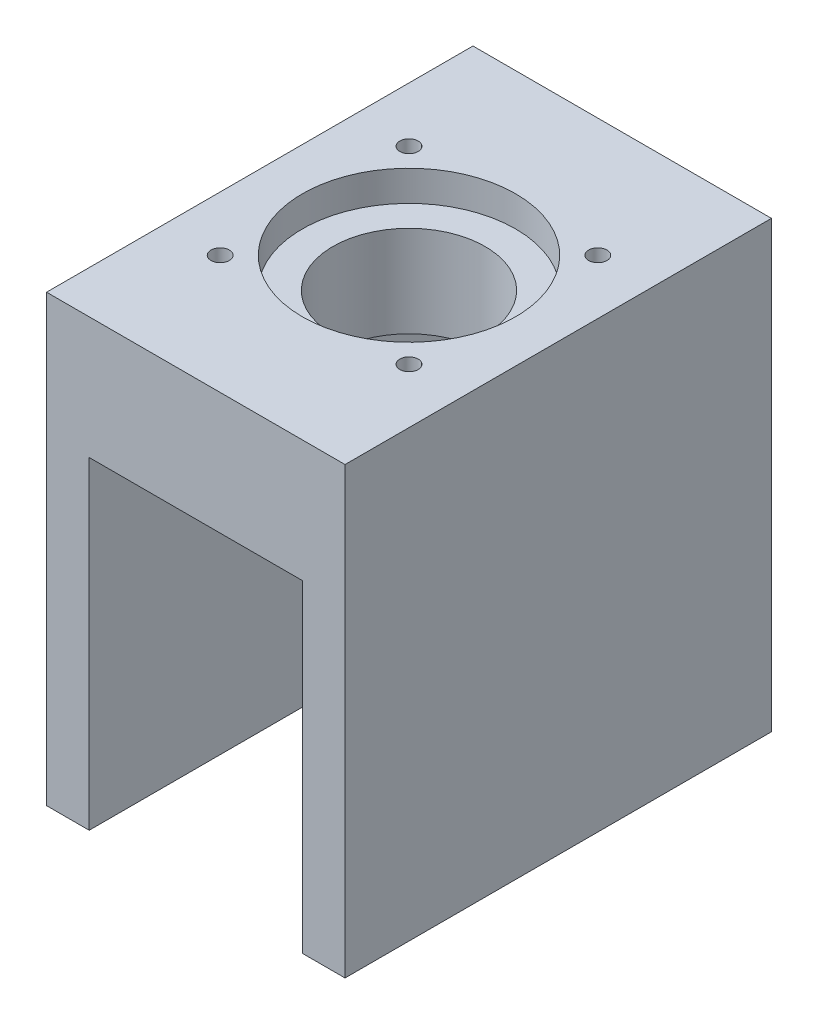
SolidWorks part; units mm, degrees
ref_plane "Front Plane" through (0, 0, 0) normal (0, 0, 1) x (1, 0, 0)
ref_plane "Top Plane" through (0, 0, 0) normal (0, 1, 0) x (1, 0, 0)
ref_plane "Right Plane" through (0, 0, 0) normal (1, 0, 0) x (0, 0, -1)
sketch "Sketch1" plane through (0, 0, 0) normal (0, 1, 0) x (1, 0, 0)
  line L1 (24.5, -35) -> (-24.5, -35)
  line L2 (24.5, -35) -> (24.5, 35)
  line L3 (24.5, 35) -> (-24.5, 35)
  line L4 (-24.5, -35) -> (-24.5, 35)
  line L5 (24.5, -35) -> (-24.5, 35) construction
  line L6 (24.5, 35) -> (-24.5, -35) construction
  point P0 (0, 0)
  dimension "D1" = 49
  dimension "D2" = 70
extrude "Boss-Extrude1" add sketch "Sketch1" along normal blind 20
sketch "Sketch3" plane through (0, 20, 0) normal (0, 1, 0) x (1, 0, 0)
  circle A0 centre (0, 0) radius 12.5
  dimension "D1" = 25
extrude "Cut-Extrude1" cut sketch "Sketch3" against normal blind 70
sketch "Sketch4" plane through (0, 0, 0) normal (0, -1, 0) x (1, 0, 0)
  circle A0 centre (-15.5, 15.5) radius 1.5
  circle A1 centre (15.5, 15.5) radius 1.5
  circle A2 centre (15.5, -15.5) radius 1.5
  circle A3 centre (-15.5, -15.5) radius 1.5
  point P12 (0, 0)
  dimension "D1" = 4
extrude "Cut-Extrude2" cut sketch "Sketch4" against normal through all
sketch "Sketch5" plane through (0, 20, 0) normal (0, 1, 0) x (1, 0, 0)
  circle A0 centre (0, 0) radius 17.5
  circle A1 centre (0, 0) radius 12.5
  dimension "D1" = 35
extrude "Cut-Extrude3" cut sketch "Sketch5" against normal blind 5
sketch "Sketch6" plane through (0, 0, 0) normal (0, -1, 0) x (1, 0, 0)
  line L0 (-24.5, -35) -> (-24.5, 35) construction
  line L1 (-24.5, 35) -> (-17.5, 35)
  line L2 (-24.5, 35) -> (-24.5, -35)
  line L3 (-24.5, -35) -> (-17.5, -35)
  line L4 (-17.5, 35) -> (-17.5, -35)
  line L5 (24.5, -35) -> (-24.5, -35) construction
  line L6 (-24.5, 35) -> (24.5, 35) construction
  line L7 (0, 0) -> (0, 15.9025) construction
  line L8 (24.5, -35) -> (17.5, -35)
  line L9 (17.5, 35) -> (17.5, -35)
  line L10 (24.5, 35) -> (17.5, 35)
  line L11 (24.5, 35) -> (24.5, -35)
  dimension "D1" = 7
extrude "Boss-Extrude3" add sketch "Sketch6" along normal blind 53
